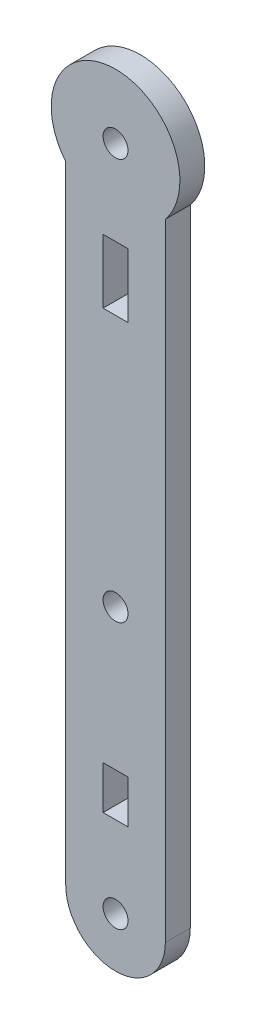
SolidWorks part; units mm, degrees
ref_plane "Plan de face" through (0, 0, 0) normal (0, 0, 1) x (1, 0, 0)
ref_plane "Plan de dessus" through (0, 0, 0) normal (0, 1, 0) x (1, 0, 0)
ref_plane "Plan de droite" through (0, 0, 0) normal (1, 0, 0) x (0, 0, -1)
sketch "Esquisse1" plane through (0, 0, 0) normal (0, 0, 1) x (1, 0, 0)
  line L0 (765.5141, 220.346) -> (765.2667, 126.6464) construction
  line L1 (765.3969, 220.4621) -> (765.3969, 122.2152) construction
  line L2 (759.3969, 207.8663) -> (759.3969, 132.4433)
  line L3 (771.3969, 207.8663) -> (771.3969, 132.4433)
  line L5 (763.8969, 202.5433) -> (766.8969, 202.5433)
  line L6 (763.8969, 202.5433) -> (763.8969, 194.8433)
  line L7 (763.8969, 194.8433) -> (766.8969, 194.8433)
  line L8 (766.8969, 202.5433) -> (766.8969, 194.8433)
  line L9 (763.8969, 147.4433) -> (766.8969, 147.4433)
  line L10 (763.8969, 147.4433) -> (763.8969, 142.2433)
  line L11 (763.8969, 142.2433) -> (766.8969, 142.2433)
  line L12 (766.8969, 147.4433) -> (766.8969, 142.2433)
  circle A0 centre (765.3969, 212.7717) radius 7.75 construction
  circle A1 centre (765.3969, 212.7717) radius 1.5
  circle A2 centre (765.3969, 164.4433) radius 1.5
  circle A3 centre (765.3969, 132.4433) radius 1.5
  circle A4 centre (765.3969, 132.4433) radius 6 construction
  arc A5 (771.3969, 207.8663) -> (759.4317, 207.8241) centre (765.3969, 212.7717) ccw
  arc A6 (771.3969, 132.4433) -> (759.3969, 132.4433) centre (765.3969, 132.4433) cw
  dimension "D2" = 15.5
  dimension "D3" = 3
  dimension "D4" = 3
  dimension "D5" = 3
  dimension "D6" = 12
  dimension "D11" = 32
  dimension "D12" = 3
  dimension "D1" = 93.7
  dimension "D7" = 6
  dimension "D8" = 765.3969
  dimension "D9" = 220.4621
  dimension "D10" = 12
  dimension "D13" = 7.7
  dimension "D14" = 3
  dimension "D15" = 5.2
  dimension "D16" = 1.5
  dimension "D17" = 1.5
  dimension "D18" = 47.4
  dimension "D19" = 15.8
  dimension "D20" = 132.4433
extrude "Boss.-Extru.1" add sketch "Esquisse1" along normal blind 3
